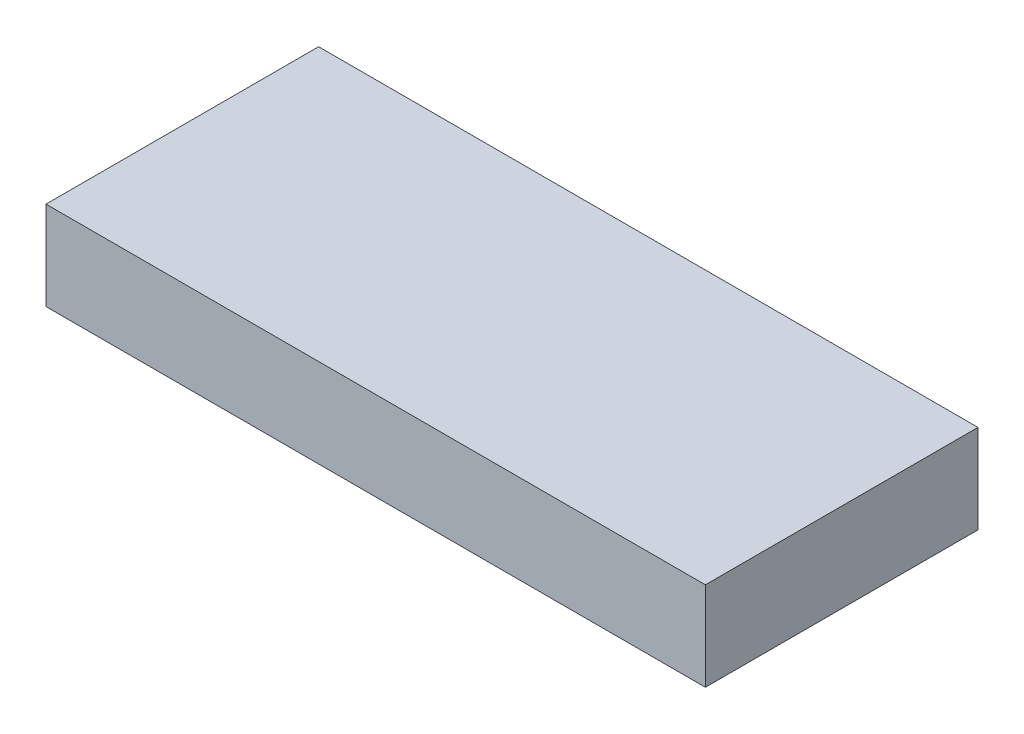
SolidWorks part; units mm, degrees
material "Hobbywing"
ref_plane "前基準面" through (0, 0, 0) normal (0, 0, 1) x (1, 0, 0)
ref_plane "上基準面" through (0, 0, 0) normal (0, 1, 0) x (1, 0, 0)
ref_plane "右基準面" through (0, 0, 0) normal (1, 0, 0) x (0, 0, -1)
sketch "草圖1" plane through (0, 0, 0) normal (0, 1, 0) x (1, 0, 0)
  line L1 (0, 0) -> (52, 0)
  line L2 (0, 0) -> (0, 21.5)
  line L3 (0, 21.5) -> (52, 21.5)
  line L4 (52, 0) -> (52, 21.5)
  dimension "D1" = 52
  dimension "D2" = 21.5
extrude "填料-伸長1" add sketch "草圖1" along normal blind 7
sketch "草圖2" plane through (0, 0, -21.5) normal (0, 0, -1) x (-1, 0, 0)
  line L0 (-26, 7) -> (-26, 0)
  line L1 (-52, 7) -> (0, 7) construction
  line L2 (-52, 0) -> (0, 0) construction
